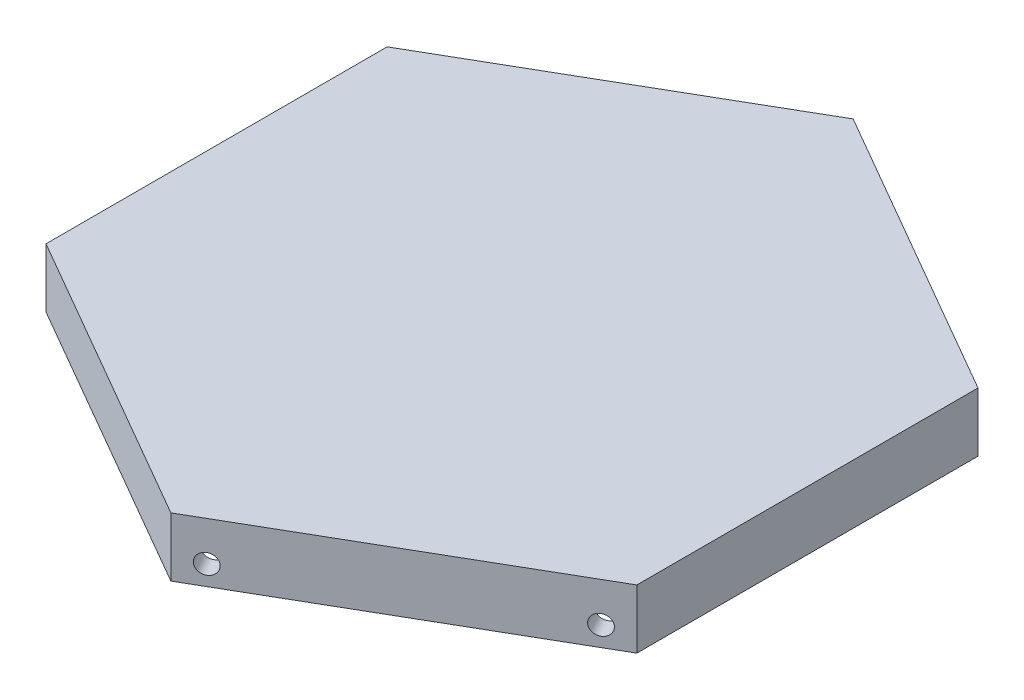
SolidWorks part; units mm, degrees
ref_plane "Front Plane" through (0, 0, 0) normal (0, 0, 1) x (1, 0, 0)
ref_plane "Top Plane" through (0, 0, 0) normal (0, 1, 0) x (1, 0, 0)
ref_plane "Right Plane" through (0, 0, 0) normal (1, 0, 0) x (0, 0, -1)
sketch "Sketch1" plane through (0, 0, 0) normal (0, 1, 0) x (1, 0, 0)
  line L1 (0, 51.9615) -> (-45, 25.9808)
  line L2 (-45, 25.9808) -> (-45, -25.9808)
  line L3 (-45, -25.9808) -> (0, -51.9615)
  line L4 (0, -51.9615) -> (45, -25.9808)
  line L5 (45, -25.9808) -> (45, 25.9808)
  line L6 (45, 25.9808) -> (0, 51.9615)
  circle A0 centre (0, 0) radius 45 construction
  dimension "D1" = 90
extrude "Boss-Extrude2" add sketch "Sketch1" along normal blind 9
sketch "Sketch4" plane through (0, 0, 0) normal (0, -1, 0) x (1, 0, 0)
  line L0 (-45, -25.9808) -> (-45, 25.9808) construction
  line L1 (0, 48.4974) -> (-42, 24.2487)
  line L2 (-42, 24.2487) -> (-42, -24.2487)
  line L3 (-42, -24.2487) -> (0, -48.4974)
  line L4 (0, -48.4974) -> (42, -24.2487)
  line L5 (42, -24.2487) -> (42, 24.2487)
  line L6 (42, 24.2487) -> (0, 48.4974)
  circle A0 centre (0, 0) radius 42 construction
  dimension "D1" = 3
extrude "Cut-Extrude3" cut sketch "Sketch4" against normal blind 6
sketch "Sketch5" plane through (-45, 0, 0) normal (-1, 0, 0) x (0, 0, 1)
  line L0 (-21.9808, 9) -> (-21.9808, 0) construction
  line L1 (-25.9808, 9) -> (25.9808, 9) construction
  line L2 (-25.9808, 0) -> (25.9808, 0) construction
  line L3 (-25.9808, 9) -> (-25.9808, 0) construction
  line L4 (0, 9) -> (0, 0) construction
  line L5 (-21.9808, 0) -> (-21.9808, 3) construction
  circle A0 centre (-21.9808, 3) radius 1.5
  circle A1 centre (21.9808, 3) radius 1.5
  dimension "D2" = 3
  dimension "D3" = 3
  dimension "D1" = 4
extrude "Cut-Extrude7" cut sketch "Sketch5" against normal blind 5
sketch "Sketch7" plane through (22.5, 0, 38.9711) normal (0.5, 0, 0.866) x (0.866, 0, -0.5)
  line L0 (-21.9808, 9) -> (-21.9808, 0) construction
  line L1 (-25.9808, 9) -> (25.9808, 9) construction
  line L2 (-25.9808, 0) -> (25.9808, 0) construction
  line L3 (-25.9808, 9) -> (-25.9808, 0) construction
  line L4 (-21.9808, 0) -> (-21.9808, 3) construction
  line L5 (0, 9) -> (0, 0) construction
  circle A0 centre (-21.9808, 3) radius 1.5
  circle A1 centre (21.9808, 3) radius 1.5
  dimension "D3" = 3
  dimension "D1" = 4
  dimension "D2" = 3
extrude "Cut-Extrude8" cut sketch "Sketch7" against normal blind 5
sketch "Sketch8" plane through (22.5, 0, -38.9711) normal (0.5, 0, -0.866) x (-0.866, 0, -0.5)
  line L0 (-21.9808, 0) -> (-21.9808, 3) construction
  line L1 (-25.9808, 0) -> (25.9808, 0) construction
  line L2 (-25.9808, 9) -> (-25.9808, 0) construction
  line L3 (0, 0) -> (0, 9) construction
  line L4 (-25.9808, 9) -> (25.9808, 9) construction
  circle A0 centre (-21.9808, 3) radius 1.5
  circle A1 centre (21.9808, 3) radius 1.5
  dimension "D3" = 3
  dimension "D1" = 4
  dimension "D2" = 3
extrude "Cut-Extrude9" cut sketch "Sketch8" against normal blind 5
